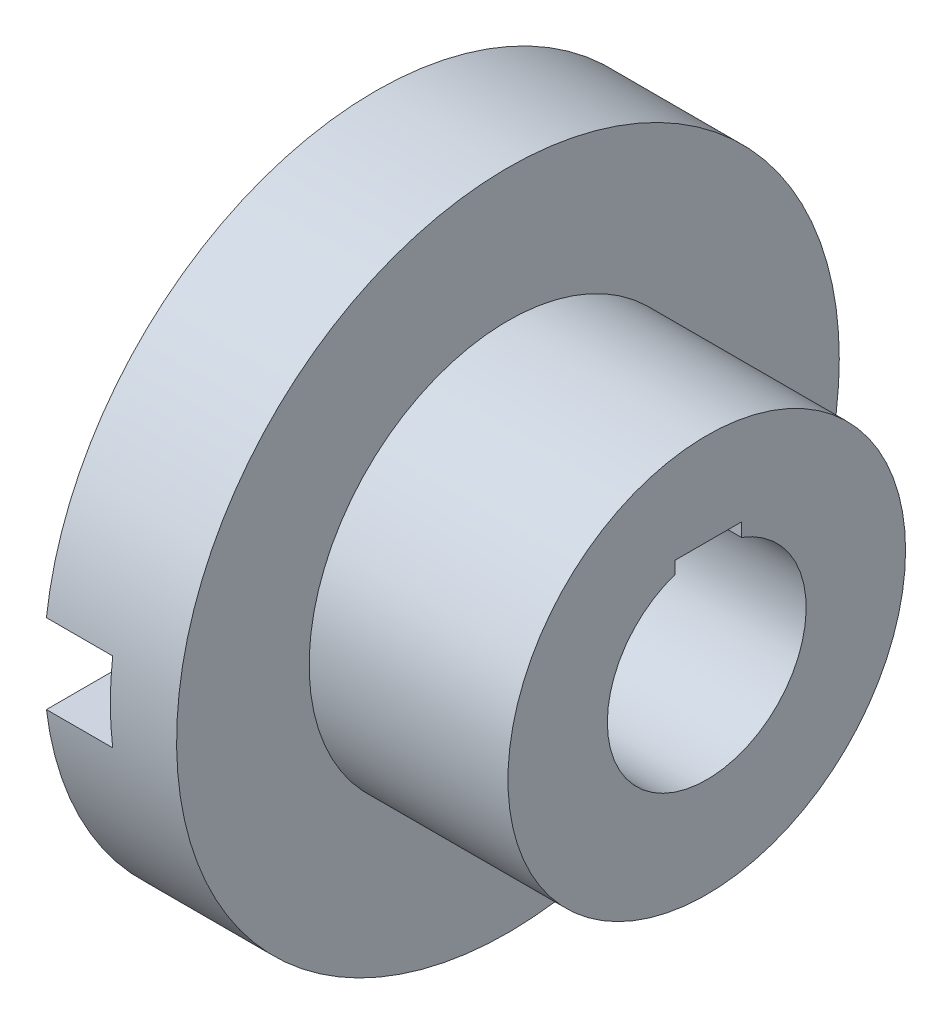
SolidWorks part; units mm, degrees
material "ABS"
ref_plane "Front Plane" through (0, 0, 0) normal (0, 0, 1) x (1, 0, 0)
ref_plane "Top Plane" through (0, 0, 0) normal (0, 1, 0) x (1, 0, 0)
ref_plane "Right Plane" through (0, 0, 0) normal (1, 0, 0) x (0, 0, -1)
sketch "Sketch1" plane through (0, 0, 0) normal (1, 0, 0) x (0, 0, -1)
  circle A0 centre (0, 0) radius 50
  dimension "D1" = 100
extrude "Boss-Extrude1" add sketch "Sketch1" along normal blind 20
sketch "Sketch2" plane through (20, 0, 0) normal (1, 0, 0) x (0, 0, -1)
  circle A0 centre (0, 0) radius 30
  dimension "D1" = 60
extrude "Boss-Extrude2" add sketch "Sketch2" along normal blind 30
sketch "Sketch3" plane through (0, 0, 0) normal (-1, 0, 0) x (0, 0, 1)
  line L1 (-5.2333, 16.0819) -> (4.7667, 16.0819)
  line L2 (-5.2333, 16.0819) -> (-5.2333, 14.0575)
  line L4 (4.7667, 16.0819) -> (4.7667, 14.2225)
  arc A0 (-5.2333, 14.0575) -> (4.7667, 14.2225) centre (0, 0) ccw
  dimension "D1" = 30
extrude "Cut-Extrude1" cut sketch "Sketch3" against normal up to surface (50 mm away) up to face at (50, 0, -30)
sketch "Sketch4" plane through (0, 0, 0) normal (-1, 0, 0) x (0, 0, 1)
  line L1 (-49.6387, 6) -> (49.6387, 6)
  line L3 (-49.6387, -6) -> (49.6387, -6)
  circle A0 centre (0, 0) radius 50 construction
  circle A1 centre (0, 0) radius 50
  arc M6 (4.7667, 14.2225) -> (-5.2333, 14.0575) centre (0, 0) cw
  circle M9 centre (0, 0) radius 50
  dimension "D1" = 12
  dimension "D2" = 6
extrude "Cut-Extrude2" cut sketch "Sketch4" against normal blind 10 contours L3 L1 M6 M9 | L3 L1 M9 M6
